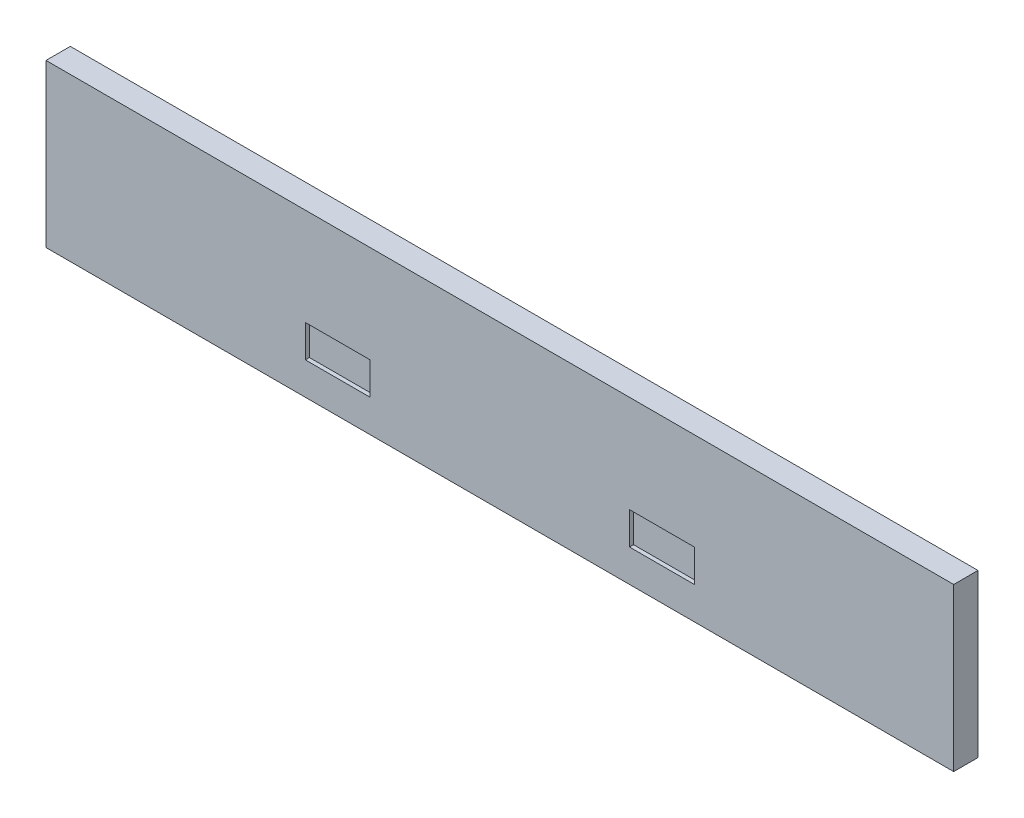
SolidWorks part; units mm, degrees
material "Pine"
ref_plane "Front Plane" through (0, 0, 0) normal (0, 0, 1) x (1, 0, 0)
ref_plane "Top Plane" through (0, 0, 0) normal (0, 1, 0) x (1, 0, 0)
ref_plane "Right Plane" through (0, 0, 0) normal (1, 0, 0) x (0, 0, -1)
sketch "Sketch1" plane through (0, 0, 0) normal (0, 0, 1) x (1, 0, 0)
  line L0 (0, -64.5222) -> (0, 64.5222) construction
  line L1 (0, 0) -> (711.2, 0)
  line L2 (0, 0) -> (0, 127)
  line L3 (0, 127) -> (711.2, 127)
  line L4 (711.2, 0) -> (711.2, 127)
  dimension "D1" = 127
  dimension "D2" = 711.2
extrude "Boss-Extrude1" add sketch "Sketch1" along normal blind 19.05
sketch "Sketch2" plane through (0, 0, 19.05) normal (0, 0, 1) x (1, 0, 0)
  line L0 (0, 127) -> (0, 0) construction
  line L1 (203.2, 50.8) -> (254, 50.8)
  line L2 (203.2, 50.8) -> (203.2, 25.4)
  line L3 (203.2, 25.4) -> (254, 25.4)
  line L4 (254, 50.8) -> (254, 25.4)
  line L5 (457.2, 50.8) -> (508, 50.8)
  line L6 (457.2, 50.8) -> (457.2, 25.4)
  line L7 (457.2, 25.4) -> (508, 25.4)
  line L8 (508, 50.8) -> (508, 25.4)
  line L9 (711.2, 0) -> (711.2, 127) construction
  line L10 (0, 0) -> (711.2, 0) construction
  dimension "D1" = 25.4
  dimension "D2" = 50.8
  dimension "D3" = 203.2
  dimension "D4" = 203.2
  dimension "D5" = 25.4
extrude "Cut-Extrude1" cut sketch "Sketch2" against normal blind 3.175
